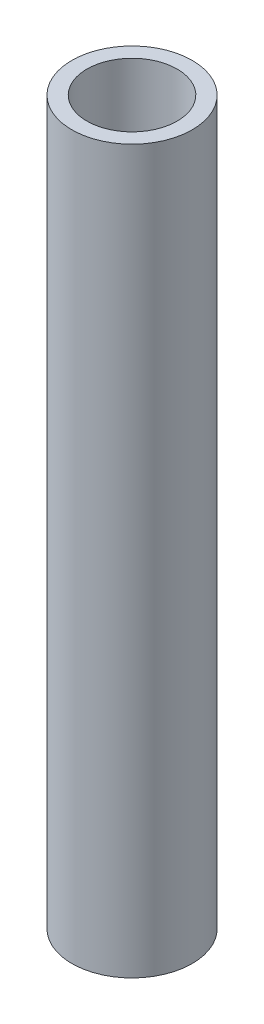
SolidWorks part; units mm, degrees
material "A-Glass Fiber"
ref_plane "Front Plane" through (0, 0, 0) normal (0, 0, 1) x (1, 0, 0)
ref_plane "Top Plane" through (0, 0, 0) normal (0, 1, 0) x (1, 0, 0)
ref_plane "Right Plane" through (0, 0, 0) normal (1, 0, 0) x (0, 0, -1)
sketch "Sketch1" plane through (0, 0, 0) normal (0, 1, 0) x (1, 0, 0)
  circle A0 centre (0, 0) radius 19.05
  circle A1 centre (0, 0) radius 25.4
  dimension "D1" = 50.8
  dimension "D2" = 38.1
extrude "Boss-Extrude1" add sketch "Sketch1" along normal blind 304.8
sketch "Sketch3" plane through (0, 0, 0) normal (0, 0, 1) x (1, 0, 0)
  line L0 (0, 0) -> (0, 51.9478) construction
  line L1 (-19.05, 0) -> (19.05, 0) construction
  line L2 (19.05, 0) -> (24.1554, 0)
  line L3 (-25.4, 0) -> (25.4, 0) construction
  line L4 (24.1554, 0) -> (24.1554, 12.7)
  line L5 (24.1554, 12.7) -> (19.05, 12.7)
  line L6 (19.05, 12.7) -> (19.05, 0)
  dimension "D1" = 38.1
  dimension "D2" = 48.3108
  dimension "D3" = 12.7
revolve "Cut-Revolve1" cut sketch "Sketch3" angle 360 about L0
